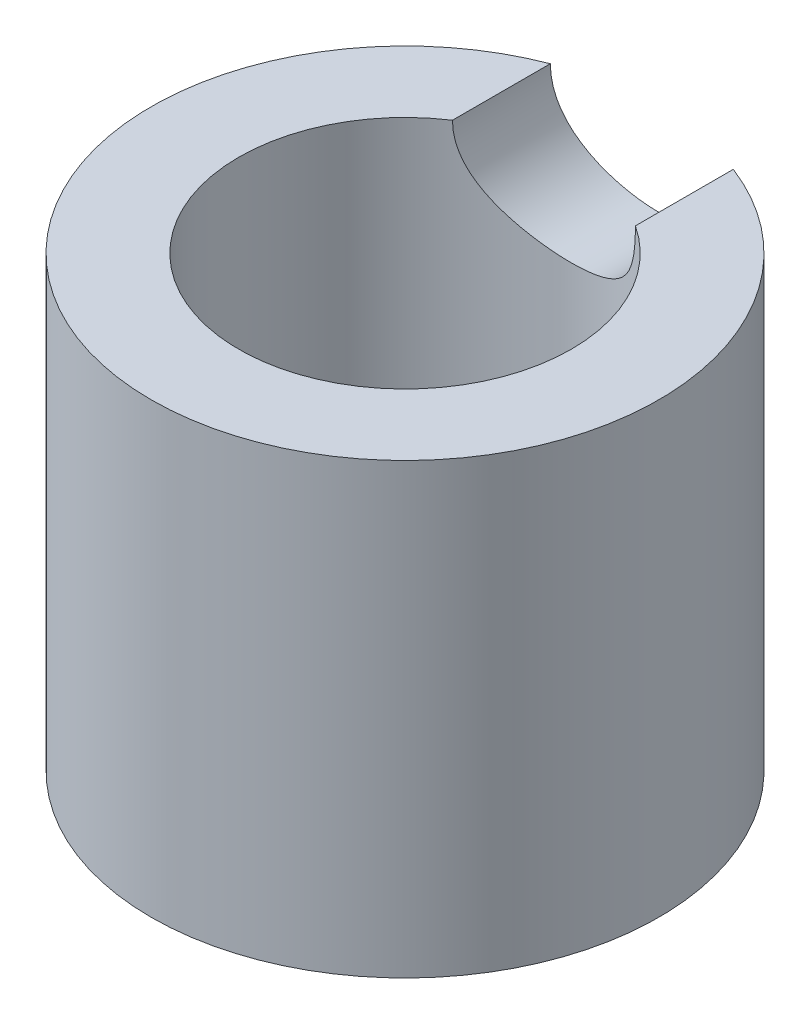
SolidWorks part; units mm, degrees
ref_plane "Front Plane" through (0, 0, 0) normal (0, 0, 1) x (1, 0, 0)
ref_plane "Top Plane" through (0, 0, 0) normal (0, 1, 0) x (1, 0, 0)
ref_plane "Right Plane" through (0, 0, 0) normal (1, 0, 0) x (0, 0, -1)
sketch "Sketch1" plane through (0, 0, 0) normal (0, 1, 0) x (1, 0, 0)
  circle A0 centre (0, 0) radius 29
  circle A1 centre (0, 0) radius 19
  dimension "D1" = 58
  dimension "D2" = 10
extrude "Boss-Extrude1" add sketch "Sketch1" along normal blind 51.2
sketch "Sketch2" plane through (0, 0, 0) normal (0, 0, 1) x (1, 0, 0)
  line L0 (29, 51.2) -> (-29, 51.2) construction
  circle A0 centre (0, 51.2) radius 10.45
  circle A1 centre (0, 0) radius 10.45
  dimension "D1" = 20.9
extrude "Cut-Extrude1" cut sketch "Sketch2" against normal through all
